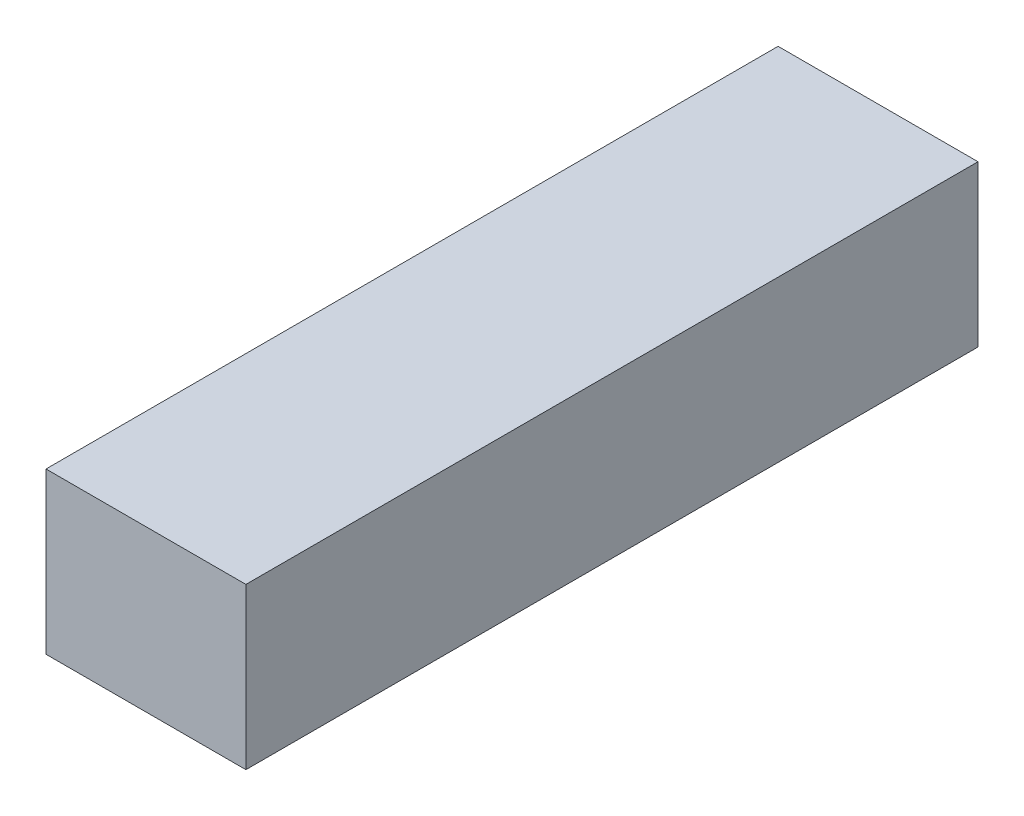
SolidWorks part; units mm, degrees
ref_plane "Front Plane" through (0, 0, 0) normal (0, 0, 1) x (1, 0, 0)
ref_plane "Top Plane" through (0, 0, 0) normal (0, 1, 0) x (1, 0, 0)
ref_plane "Right Plane" through (0, 0, 0) normal (1, 0, 0) x (0, 0, -1)
sketch "Sketch1" plane through (0, 0, 0) normal (0, 1, 0) x (1, 0, 0)
  line L1 (-6.2286, -22.8103) -> (6.2286, -22.8103)
  line L2 (-6.2286, -22.8103) -> (-6.2286, 22.8103)
  line L3 (-6.2286, 22.8103) -> (6.2286, 22.8103)
  line L4 (6.2286, -22.8103) -> (6.2286, 22.8103)
  line L5 (-6.2286, -22.8103) -> (6.2286, 22.8103) construction
  line L6 (-6.2286, 22.8103) -> (6.2286, -22.8103) construction
  point P0 (0, 0)
extrude "Boss-Extrude1" add sketch "Sketch1" along normal blind 10
